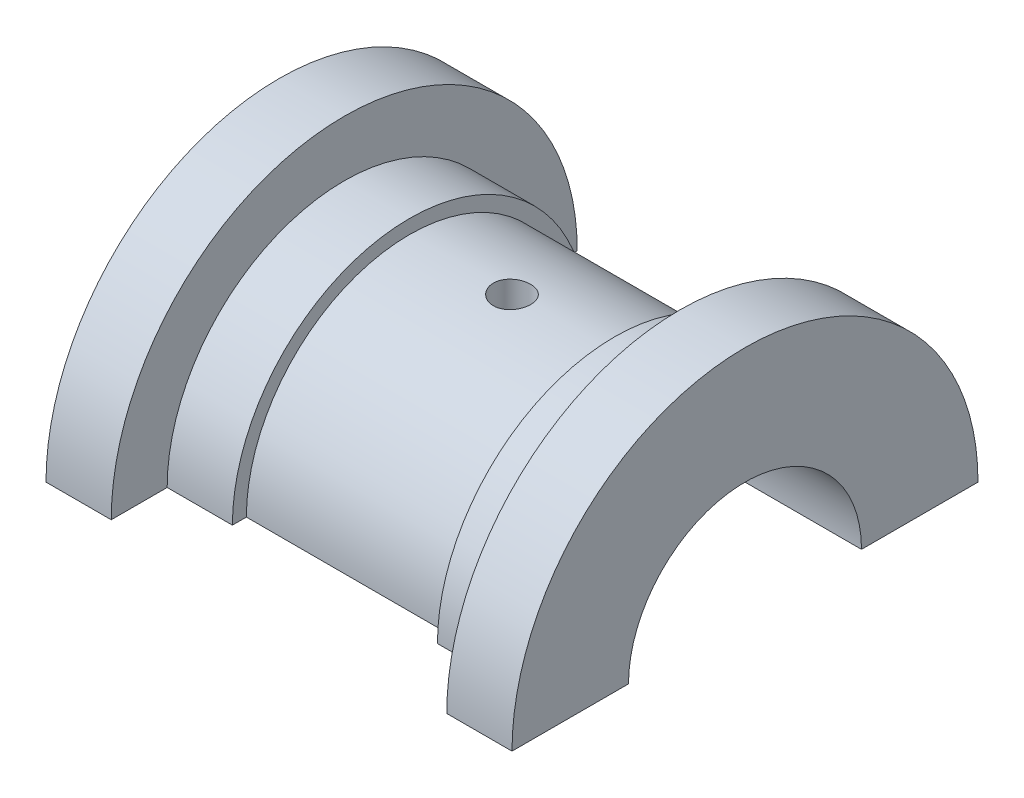
SolidWorks part; units mm, degrees
ref_plane "Front Plane" through (0, 0, 0) normal (0, 0, 1) x (1, 0, 0)
ref_plane "Top Plane" through (0, 0, 0) normal (0, 1, 0) x (1, 0, 0)
ref_plane "Right Plane" through (0, 0, 0) normal (1, 0, 0) x (0, 0, -1)
sketch "Sketch1" plane through (0, 0, 0) normal (0, 0, 1) x (1, 0, 0)
  line L0 (-25, 0) -> (25, 0)
  line L1 (25, 0) -> (25, 25)
  line L2 (25, 25) -> (18, 25)
  line L3 (18, 25) -> (18, 19)
  line L4 (18, 19) -> (11, 19)
  line L5 (11, 19) -> (11, 17.5)
  line L6 (11, 17.5) -> (-11, 17.5)
  line L8 (-11, 19) -> (-11, 17.5)
  line L9 (-18, 19) -> (-11, 19)
  line L10 (-18, 25) -> (-18, 19)
  line L11 (-25, 25) -> (-18, 25)
  line L12 (-25, 0) -> (-25, 25)
  dimension "D2" = 25
  dimension "D4" = 1.5
  dimension "D5" = 6
  dimension "D7" = 7
  dimension "D8" = 7
revolve "Revolve1" add sketch "Sketch1" angle 360 about L0
sketch "Sketch2" plane through (25, 0, 0) normal (1, 0, 0) x (0, 0, -1)
  circle A0 centre (0, 0) radius 12.5
extrude "Cut-Extrude1" cut sketch "Sketch2" against normal through all
sketch "Sketch3" plane through (25, 0, 0) normal (1, 0, 0) x (0, 0, -1)
  line L0 (-25, 0) -> (25, 0)
  circle A0 centre (0, 0) radius 25 construction
extrude "Cut-Extrude2" cut sketch "Sketch3" against normal through all and the other way through all flip side to cut
ref_plane "Plane1" through (0, 17.5, 0) normal (0, 1, 0) x (1, 0, 0)
sketch "Sketch4" plane through (0, 17.5, 0) normal (0, 1, 0) x (1, 0, 0)
  circle A0 centre (0, 0) radius 2
extrude "Cut-Extrude3" cut sketch "Sketch4" against normal through all
